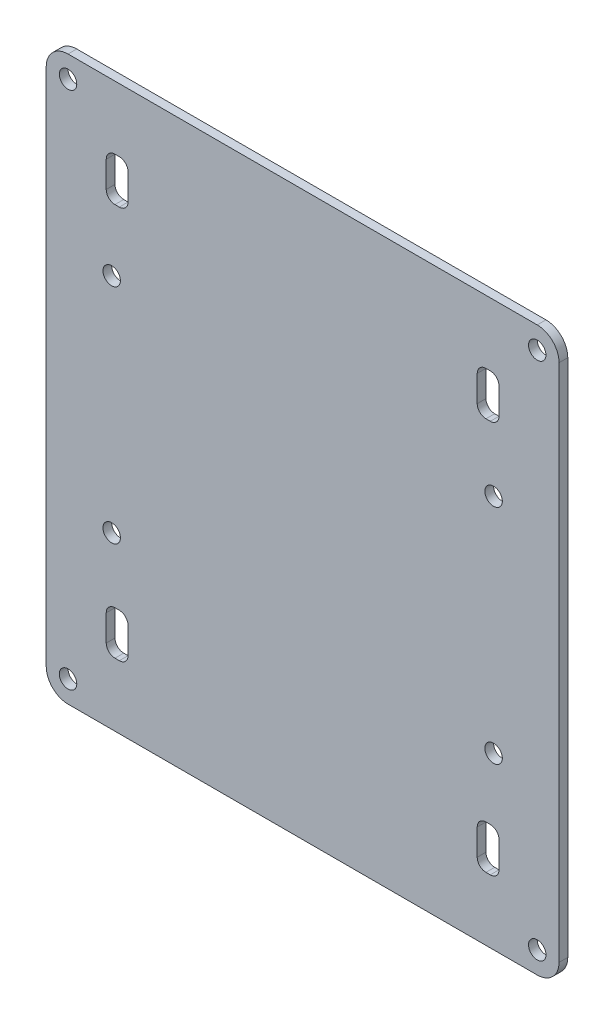
SolidWorks part; units mm, degrees
ref_plane "Front Plane" through (0, 0, 0) normal (0, 0, 1) x (1, 0, 0)
ref_plane "Top Plane" through (0, 0, 0) normal (0, 1, 0) x (1, 0, 0)
ref_plane "Right Plane" through (0, 0, 0) normal (1, 0, 0) x (0, 0, -1)
sketch "Sketch1" plane through (0, 0, 0) normal (0, 0, 1) x (1, 0, 0)
  line L1 (69, -42.5) -> (176.5, -42.5)
  line L2 (64, -47.5) -> (64, -166.5)
  line L3 (69, -171.5) -> (176.5, -171.5)
  line L4 (181.5, -47.5) -> (181.5, -166.5)
  arc A0 (64, -166.5) -> (69, -171.5) centre (69, -166.5) ccw
  arc A1 (176.5, -171.5) -> (181.5, -166.5) centre (176.5, -166.5) ccw
  arc A2 (176.5, -42.5) -> (181.5, -47.5) centre (176.5, -47.5) cw
  arc A3 (69, -42.5) -> (64, -47.5) centre (69, -47.5) ccw
  circle A8 centre (166.5, -81.5) radius 2
  circle A9 centre (166.5, -132.5) radius 2
  circle A10 centre (79, -132.5) radius 2
  circle A11 centre (79, -81.5) radius 2
  circle A16 centre (69, -166.5) radius 2
  circle A17 centre (176.5, -166.5) radius 2
  circle A18 centre (176.5, -47.5) radius 2
  circle A19 centre (69, -47.5) radius 2
extrude "Boss-Extrude1" add sketch "Sketch1" along normal blind 2
sketch "Sketch2" plane through (0, 0, 2) normal (0, 0, 1) x (1, 0, 0)
  line L0 (122.75, -42.5) -> (122.75, -171.5) construction
  line L1 (79.75, -57) -> (80.75, -57)
  line L2 (77.75, -59) -> (77.75, -65)
  line L3 (79.75, -67) -> (80.75, -67)
  line L4 (82.75, -59) -> (82.75, -65)
  line L5 (176.5, -42.5) -> (69, -42.5) construction
  line L6 (69, -171.5) -> (176.5, -171.5) construction
  line L7 (64, -107) -> (181.5, -107) construction
  line L8 (64, -47.5) -> (64, -166.5) construction
  line L9 (181.5, -166.5) -> (181.5, -47.5) construction
  line L10 (162.75, -59) -> (162.75, -65)
  line L11 (165.75, -67) -> (164.75, -67)
  line L12 (167.75, -59) -> (167.75, -65)
  line L13 (165.75, -57) -> (164.75, -57)
  line L14 (165.75, -157) -> (164.75, -157)
  line L15 (167.75, -155) -> (167.75, -149)
  line L16 (165.75, -147) -> (164.75, -147)
  line L17 (162.75, -155) -> (162.75, -149)
  line L18 (82.75, -155) -> (82.75, -149)
  line L19 (79.75, -147) -> (80.75, -147)
  line L20 (77.75, -155) -> (77.75, -149)
  line L21 (79.75, -157) -> (80.75, -157)
  arc A0 (77.75, -155) -> (79.75, -157) centre (79.75, -155) ccw
  arc A1 (79.75, -147) -> (77.75, -149) centre (79.75, -149) ccw
  arc A2 (82.75, -149) -> (80.75, -147) centre (80.75, -149) ccw
  arc A3 (82.75, -155) -> (80.75, -157) centre (80.75, -155) cw
  arc A4 (164.75, -157) -> (162.75, -155) centre (164.75, -155) cw
  arc A5 (164.75, -147) -> (162.75, -149) centre (164.75, -149) ccw
  arc A6 (167.75, -149) -> (165.75, -147) centre (165.75, -149) ccw
  arc A7 (165.75, -157) -> (167.75, -155) centre (165.75, -155) ccw
  arc A8 (167.75, -59) -> (165.75, -57) centre (165.75, -59) ccw
  arc A9 (162.75, -59) -> (164.75, -57) centre (164.75, -59) cw
  arc A10 (162.75, -65) -> (164.75, -67) centre (164.75, -65) ccw
  arc A11 (165.75, -67) -> (167.75, -65) centre (165.75, -65) ccw
  arc A12 (77.75, -65) -> (79.75, -67) centre (79.75, -65) ccw
  arc A13 (80.75, -67) -> (82.75, -65) centre (80.75, -65) ccw
  arc A14 (80.75, -57) -> (82.75, -59) centre (80.75, -59) cw
  arc A15 (79.75, -57) -> (77.75, -59) centre (79.75, -59) ccw
  point P30 (77.75, -157)
  point P33 (77.75, -147)
  point P36 (82.75, -147)
  point P39 (82.75, -157)
  point P42 (162.75, -157)
  point P45 (162.75, -147)
  point P48 (167.75, -147)
  point P51 (167.75, -157)
  point P54 (167.75, -57)
  point P57 (162.75, -57)
  point P60 (162.75, -67)
  point P63 (167.75, -67)
  point P66 (77.75, -67)
  point P69 (82.75, -67)
  point P72 (82.75, -57)
  point P75 (77.75, -57)
  dimension "D5" = 2
  dimension "D1" = 5
  dimension "D2" = 10
  dimension "D3" = 40
  dimension "D4" = 40
extrude "Cut-Extrude1" cut sketch "Sketch2" against normal blind 3
